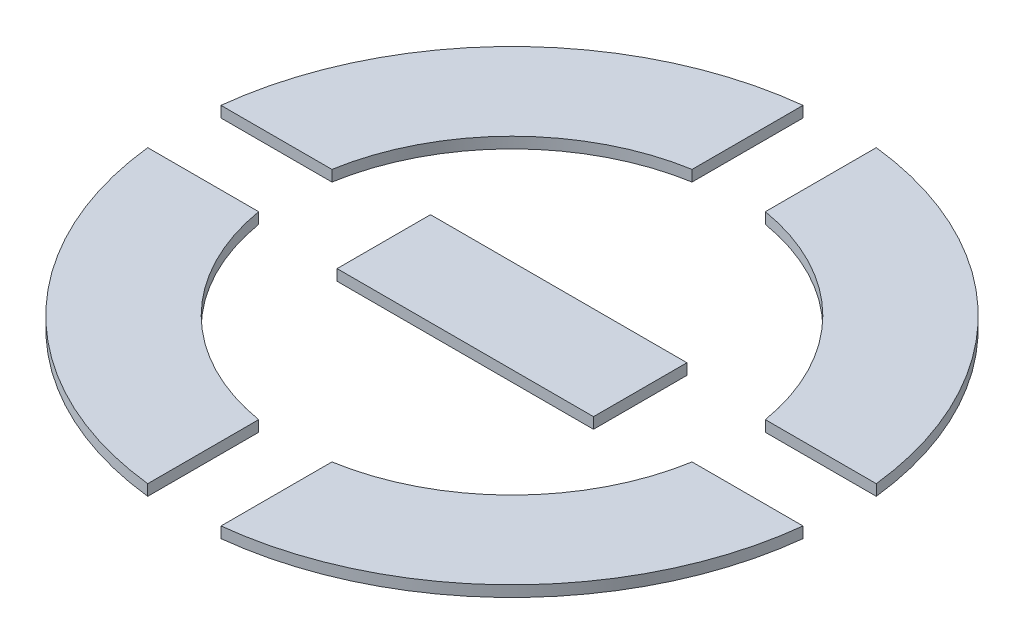
SolidWorks part; units mm, degrees
ref_plane "Front Plane" through (0, 0, 0) normal (0, 0, 1) x (1, 0, 0)
ref_plane "Top Plane" through (0, 0, 0) normal (0, 1, 0) x (1, 0, 0)
ref_plane "Right Plane" through (0, 0, 0) normal (1, 0, 0) x (0, 0, -1)
sketch "Sketch1" plane through (0, 0, 0) normal (0, 1, 0) x (1, 0, 0)
  line L0 (-10, 59.1608) -> (-10, 89.4427)
  line L1 (10, 59.1608) -> (10, 89.4427)
  line L2 (-59.1608, 10) -> (-89.4427, 10)
  line L4 (59.1608, 10) -> (89.4427, 10)
  line L5 (10, -59.1608) -> (10, -89.4427)
  line L6 (-10, -59.1608) -> (-10, -89.4427)
  line L7 (-59.1608, -10) -> (-89.4427, -10)
  line L8 (59.1608, -10) -> (89.4427, -10)
  line L9 (-35, 12.75) -> (35, 12.75)
  line L10 (-35, 12.75) -> (-35, -12.75)
  line L11 (-35, -12.75) -> (35, -12.75)
  line L12 (35, 12.75) -> (35, -12.75)
  line L13 (-35, 12.75) -> (35, -12.75) construction
  line L14 (-35, -12.75) -> (35, 12.75) construction
  arc A0 (-59.1608, -10) -> (-10, -59.1608) centre (0, 0) ccw
  arc A1 (-89.4427, -10) -> (-10, -89.4427) centre (0, 0) ccw
  arc A2 (59.1608, 10) -> (10, 59.1608) centre (0, 0) ccw
  arc A3 (89.4427, 10) -> (10, 89.4427) centre (0, 0) ccw
  arc A4 (-10, 59.1608) -> (-59.1608, 10) centre (0, 0) ccw
  arc A5 (-10, 89.4427) -> (-89.4427, 10) centre (0, 0) ccw
  arc A6 (10, -59.1608) -> (59.1608, -10) centre (0, 0) ccw
  arc A7 (10, -89.4427) -> (89.4427, -10) centre (0, 0) ccw
  dimension "D1" = 120
  dimension "D2" = 180
  dimension "D3" = 10
  dimension "D4" = 20
  dimension "D5" = 10
  dimension "D6" = 25.5
  dimension "D7" = 70
extrude "Boss-Extrude1" add sketch "Sketch1" along normal blind 3
